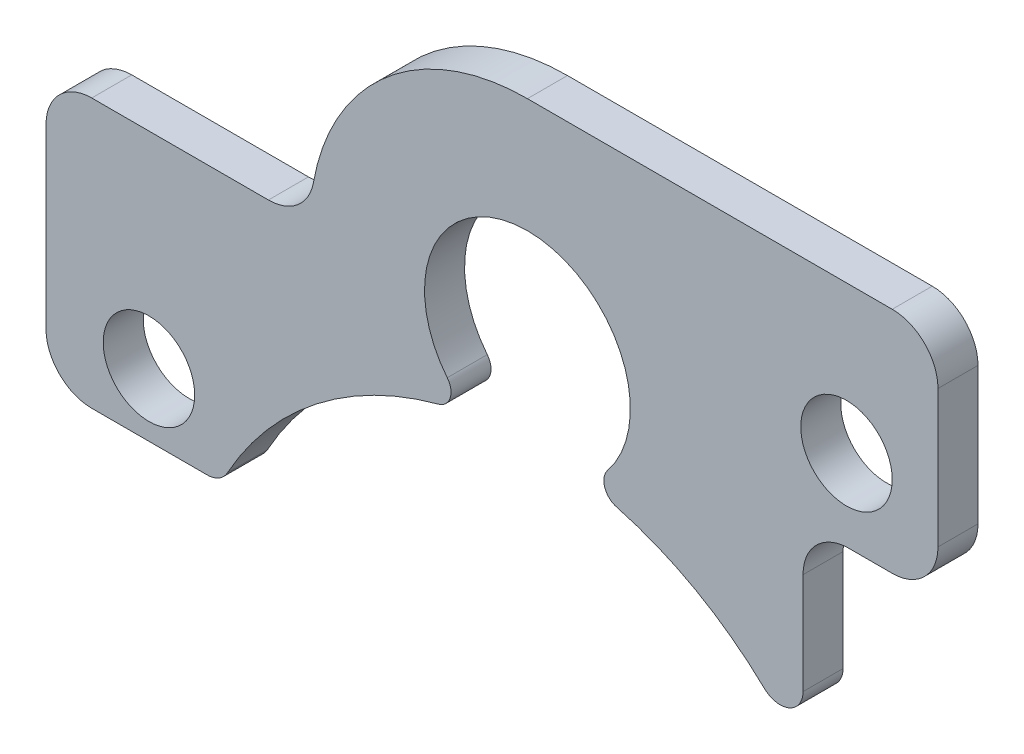
SolidWorks part; units mm, degrees
ref_plane "Front Plane" through (0, 0, 0) normal (0, 0, 1) x (1, 0, 0)
ref_plane "Top Plane" through (0, 0, 0) normal (0, 1, 0) x (1, 0, 0)
ref_plane "Right Plane" through (0, 0, 0) normal (1, 0, 0) x (0, 0, -1)
sketch "Sketch1" plane through (0, 0, 0) normal (0, 0, 1) x (1, 0, 0)
  line L6 (0, 9.5) -> (15.95, 9.5)
  line L7 (12.05, -2.6213) -> (12.05, -2.5)
  line L8 (12.05, -2.6213) -> (12.05, -6.9286)
  line L9 (-19.05, -11.75) -> (-13.9978, -11.75)
  line L10 (-21.05, -2) -> (-21.05, -9.75)
  line L11 (-11.3248, 0) -> (-19.05, 0)
  line L12 (14.05, -0.5) -> (15.95, -0.5)
  line L14 (17.95, 1.5) -> (17.95, 7.5)
  arc A16 (0, 9.5) -> (-9.3552, 1.6522) centre (0, 0) ccw
  arc A17 (17.95, 7.5) -> (15.95, 9.5) centre (15.95, 7.5) ccw
  arc A18 (10.3594, -7.6518) -> (12.05, -6.9286) centre (11.05, -6.9286) ccw
  arc A19 (10.3594, -7.6518) -> (3.896, -4.0148) centre (0, -18.5) ccw
  arc A20 (15.95, -0.5) -> (17.95, 1.5) centre (15.95, 1.5) ccw
  arc A21 (3.5064, -2.8205) -> (3.896, -4.0148) centre (4.0908, -3.2905) ccw
  arc A22 (3.5064, -2.8205) -> (3.95, 2.1558) centre (0, 0) ccw
  arc A23 (3.95, 2.1558) -> (-3.5064, -2.8205) centre (0, 0) ccw
  arc A24 (-3.896, -4.0148) -> (-3.5064, -2.8205) centre (-4.0908, -3.2905) ccw
  arc A25 (-3.896, -4.0148) -> (-13.1229, -11.2344) centre (0, -18.5) ccw
  arc A26 (-13.9978, -11.75) -> (-13.1229, -11.2344) centre (-13.9978, -10.75) ccw
  arc A27 (-21.05, -9.75) -> (-19.05, -11.75) centre (-19.05, -9.75) ccw
  arc A28 (-19.05, 0) -> (-21.05, -2) centre (-19.05, -2) ccw
  arc A29 (-11.3248, 0) -> (-9.3552, 1.6522) centre (-11.3248, 2) ccw
  circle A31 centre (-16.55, -9) radius 2
  arc A32 (14.05, -0.5) -> (12.05, -2.5) centre (14.05, -2.5) ccw
  circle A34 centre (13.95, 3.05) radius 2
  point P43 (17.95, -0.5)
  dimension "D1" = 2
  dimension "D2" = 2
extrude "Boss-Extrude2" add sketch "Sketch1" along normal blind 1.75
